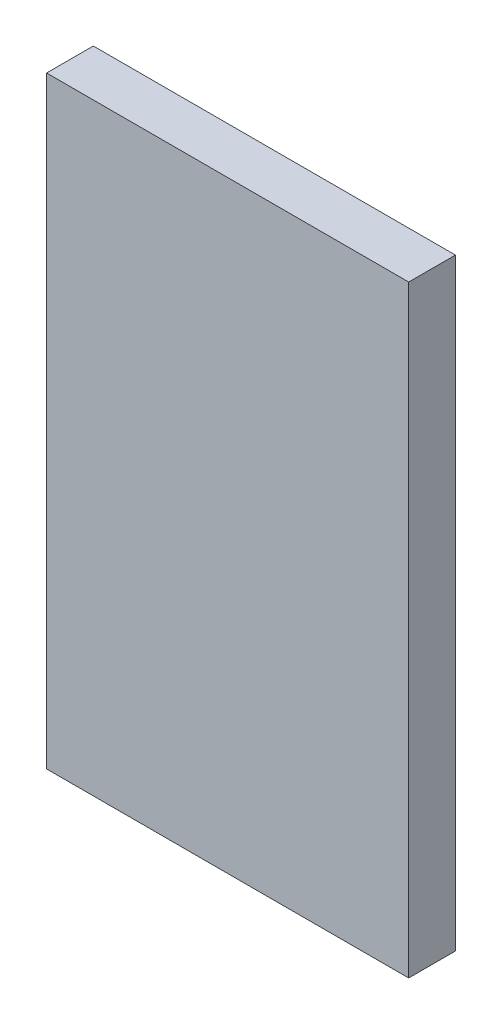
SolidWorks part; units mm, degrees
ref_plane "Alzado" through (0, 0, 0) normal (0, 0, 1) x (1, 0, 0)
ref_plane "Planta" through (0, 0, 0) normal (0, 1, 0) x (1, 0, 0)
ref_plane "Vista lateral" through (0, 0, 0) normal (1, 0, 0) x (0, 0, -1)
sketch "Croquis1" plane through (0, 0, 0) normal (0, 0, 1) x (1, 0, 0)
  line L1 (7.75, -12.9) -> (-7.75, -12.9)
  line L2 (7.75, -12.9) -> (7.75, 12.9)
  line L3 (7.75, 12.9) -> (-7.75, 12.9)
  line L4 (-7.75, -12.9) -> (-7.75, 12.9)
  line L5 (7.75, -12.9) -> (-7.75, 12.9) construction
  line L6 (7.75, 12.9) -> (-7.75, -12.9) construction
  point P0 (0, 0)
  dimension "D1" = 15.5
  dimension "D2" = 25.8
extrude "Saliente-Extruir1" add sketch "Croquis1" along normal blind 2
